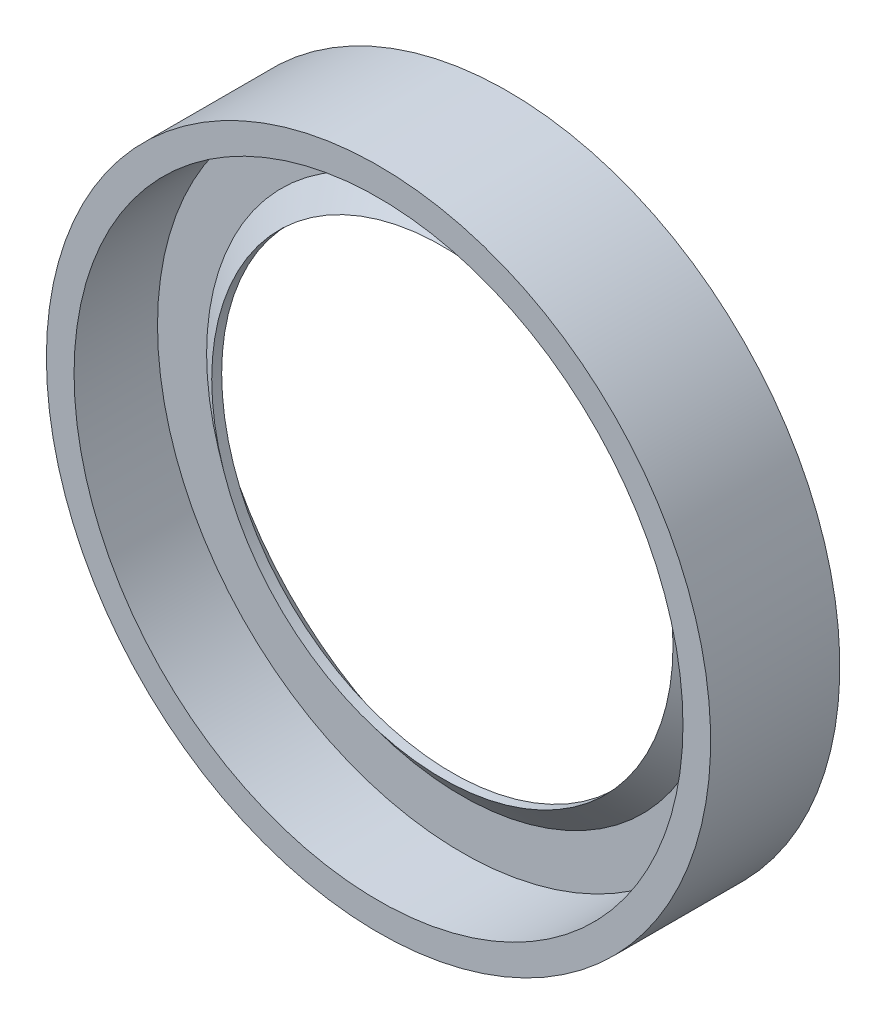
SolidWorks part; units mm, degrees
material "Rubber"
ref_plane "Front Plane" through (0, 0, 0) normal (0, 0, 1) x (1, 0, 0)
ref_plane "Top Plane" through (0, 0, 0) normal (0, 1, 0) x (1, 0, 0)
ref_plane "Right Plane" through (0, 0, 0) normal (1, 0, 0) x (0, 0, -1)
sketch "Sketch1" plane through (0, 0, 0) normal (1, 0, 0) x (0, 0, -1)
  line L0 (48.3596, 0) -> (-30.0288, 0) construction
  line L1 (0, 16.5) -> (0, 18)
  line L2 (0, 18) -> (7, 18)
  line L3 (7, 18) -> (7, 16.5)
  line L4 (7, 16.5) -> (4, 12.5)
  line L6 (4.5228, 13.8398) -> (4.5228, 16.5)
  line L7 (4.5228, 16.5) -> (0, 16.5)
  line L8 (4, 12.5) -> (3.4602, 12.5)
  line L9 (3.4602, 12.5) -> (4.5228, 13.8398)
  dimension "D1" = 36
  dimension "D2" = 25
  dimension "D3" = 1.5
  dimension "D4" = 7
  dimension "D5" = 4
revolve "Revolve1" add sketch "Sketch1" angle 360 about L0
other "Freeze***"
